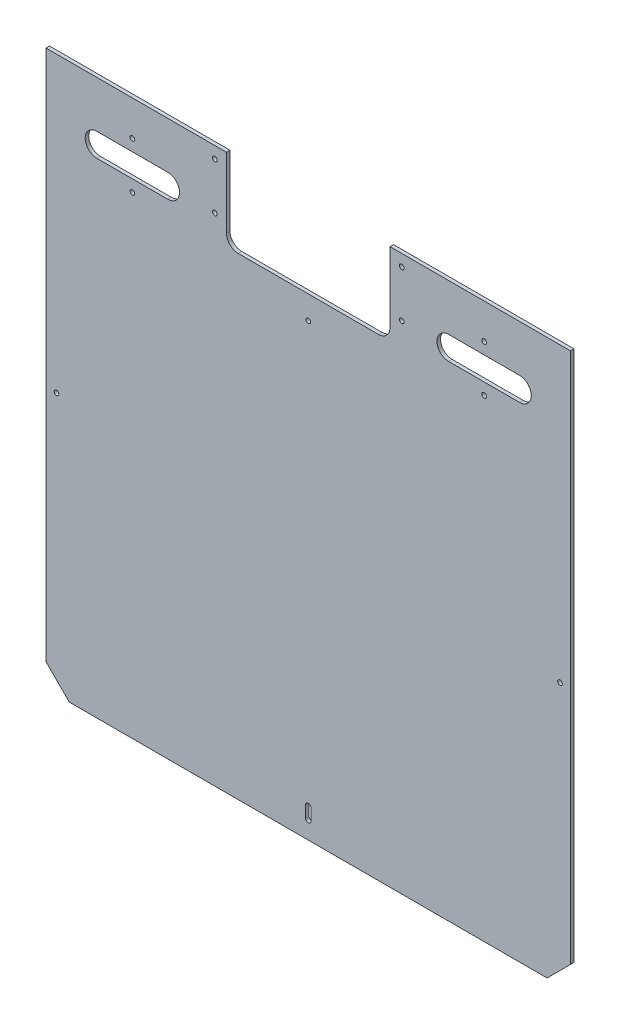
SolidWorks part; units mm, degrees
ref_plane "Piano frontale" through (0, 0, 0) normal (0, 0, 1) x (1, 0, 0)
ref_plane "Piano superiore" through (0, 0, 0) normal (0, 1, 0) x (1, 0, 0)
ref_plane "Piano destro" through (0, 0, 0) normal (1, 0, 0) x (0, 0, -1)
sketch "Schizzo1" plane through (0, 0, 0) normal (0, 0, 1) x (1, 0, 0)
  line L0 (0, 20) -> (0, 475)
  line L1 (0, 475) -> (154.5, 475)
  line L2 (449, 475) -> (449, 20)
  line L3 (429, 0) -> (20, 0)
  line L4 (154.5, 475) -> (154.5, 415)
  line L5 (164.5, 405) -> (284.5, 405)
  line L6 (294.5, 415) -> (294.5, 475)
  line L7 (294.5, 475) -> (449, 475)
  line L8 (154.5, 425) -> (294.5, 425) construction
  line L9 (224.5, 379) -> (224.5, 419) construction
  line L10 (344.7159, 425) -> (405.4404, 425) construction
  line L11 (344.7159, 435) -> (405.4404, 435)
  line L12 (344.7159, 415) -> (405.4404, 415)
  line L13 (104.2841, 425) -> (43.5596, 425) construction
  line L14 (104.2841, 435) -> (43.5596, 435)
  line L15 (104.2841, 415) -> (43.5596, 415)
  line L16 (0, 0) -> (224.5, 224.5) construction
  line L17 (224.5, 224.5) -> (449, 0) construction
  line L18 (224.5, 15) -> (224.5, 25) construction
  line L19 (222.25, 15) -> (222.25, 25)
  line L20 (226.75, 15) -> (226.75, 25)
  line L21 (20, 0) -> (0, 20)
  line L22 (449, 20) -> (429, 0)
  line L23 (73.9219, 425) -> (73.9219, 475) construction
  line L24 (154.5, 445) -> (294.5, 445) construction
  arc A0 (154.5, 415) -> (164.5, 405) centre (164.5, 415) ccw
  arc A1 (294.5, 415) -> (284.5, 405) centre (284.5, 415) cw
  circle A2 centre (144.5, 425) radius 2
  circle A3 centre (224.5, 385) radius 2
  circle A4 centre (73.9219, 445) radius 2
  circle A5 centre (9, 223.8264) radius 2
  circle A6 centre (440, 224.5) radius 2
  circle A7 centre (73.9219, 405) radius 2
  arc A8 (344.7159, 435) -> (344.7159, 415) centre (344.7159, 425) ccw
  arc A9 (405.4404, 415) -> (405.4404, 435) centre (405.4404, 425) ccw
  arc A10 (104.2841, 435) -> (104.2841, 415) centre (104.2841, 425) cw
  arc A11 (43.5596, 415) -> (43.5596, 435) centre (43.5596, 425) cw
  arc A14 (222.25, 15) -> (226.75, 15) centre (224.5, 15) ccw
  arc A15 (226.75, 25) -> (222.25, 25) centre (224.5, 25) ccw
  circle A16 centre (375.0781, 405) radius 2
  circle A17 centre (375.0781, 445) radius 2
  circle A18 centre (144.5, 465) radius 2
  circle A19 centre (304.5, 425) radius 2
  circle A20 centre (304.5, 465) radius 2
  point P11 (154.5, 405)
  point P14 (294.5, 405)
  point P33 (375.0781, 425)
  point P40 (73.9219, 425)
  point P52 (224.5, 20)
  dimension "D5" = 10
  dimension "D6" = 4
  dimension "D7" = 4
  dimension "D8" = 4
  dimension "D9" = 4
  dimension "D10" = 90
  dimension "D22" = 4
  dimension "D1" = 449
  dimension "D2" = 475
  dimension "D3" = 140
  dimension "D4" = 70
  dimension "D11" = 20
  dimension "D13" = 9
  dimension "D14" = 9
  dimension "D15" = 4.5
  dimension "D16" = 10
  dimension "D17" = 15
  dimension "D18" = 80
  dimension "D21" = 50
  dimension "D23" = 20
extrude "Estrusione-Estrusione1" add sketch "Schizzo1" along normal blind 3
